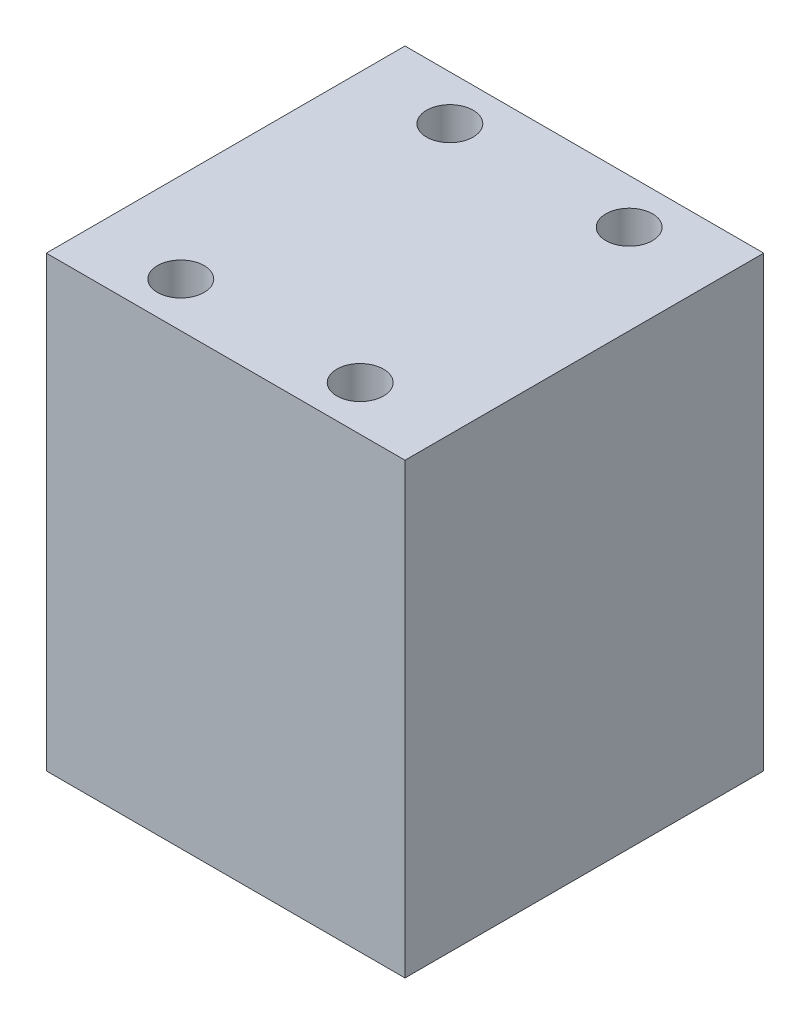
SolidWorks part; units mm, degrees
ref_plane "前视基准面" through (0, 0, 0) normal (0, 0, 1) x (1, 0, 0)
ref_plane "上视基准面" through (0, 0, 0) normal (0, 1, 0) x (1, 0, 0)
ref_plane "右视基准面" through (0, 0, 0) normal (1, 0, 0) x (0, 0, -1)
sketch "草图1" plane through (0, 0, 0) normal (0, 1, 0) x (1, 0, 0)
  line L1 (-20, 20) -> (20, 20)
  line L2 (-20, 20) -> (-20, -20)
  line L3 (-20, -20) -> (20, -20)
  line L4 (20, 20) -> (20, -20)
  line L5 (-20, 20) -> (20, -20) construction
  line L6 (-20, -20) -> (20, 20) construction
  point P0 (0, 0)
extrude "凸台-拉伸2" add sketch "草图1" along normal blind 50
sketch "草图2" plane through (0, 50, 0) normal (0, 1, 0) x (1, 0, 0)
  circle A0 centre (10, 15) radius 2.6
  circle A1 centre (-10, 15) radius 2.6
  circle A2 centre (-10, -15) radius 2.6
  circle A3 centre (10, -15) radius 2.6
extrude "切除-拉伸1" cut sketch "草图2" against normal through all
